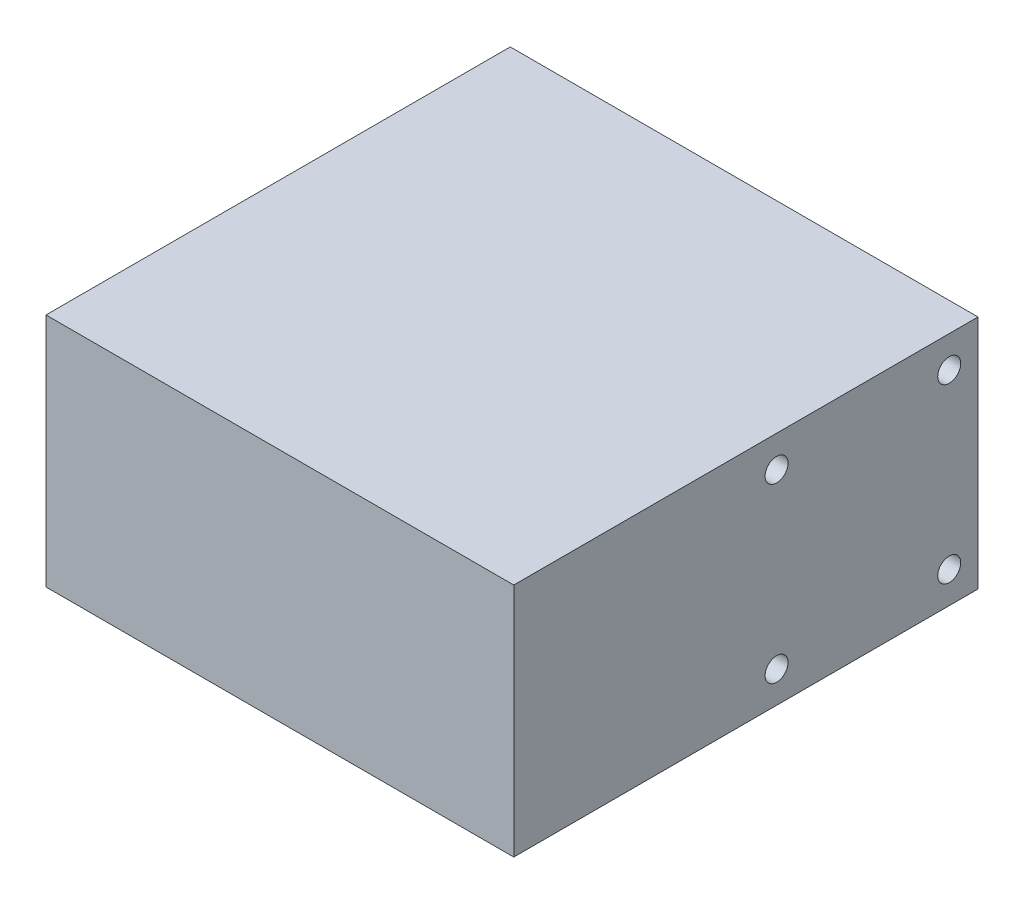
SolidWorks part; units mm, degrees
ref_plane "Front Plane" through (0, 0, 0) normal (0, 0, 1) x (1, 0, 0)
ref_plane "Top Plane" through (0, 0, 0) normal (0, 1, 0) x (1, 0, 0)
ref_plane "Right Plane" through (0, 0, 0) normal (1, 0, 0) x (0, 0, -1)
sketch "Sketch1" plane through (0, 0, 0) normal (0, 1, 0) x (1, 0, 0)
  line L1 (0, 0) -> (40.64, 0)
  line L2 (0, 0) -> (0, 40.3352)
  line L3 (0, 40.3352) -> (40.64, 40.3352)
  line L4 (40.64, 0) -> (40.64, 40.3352)
  dimension "D1" = 40.3352
  dimension "D2" = 40.64
extrude "Boss-Extrude1" add sketch "Sketch1" along normal blind 20.4724
sketch "Sketch3" plane through (0, 0, 0) normal (-1, 0, 0) x (0, 0, 1)
  line L0 (-40.3352, 20.4724) -> (0, 20.4724) construction
  line L2 (0, 20.4724) -> (0, 0) construction
  circle A0 centre (-10.541, 10.2362) radius 2.921
  circle A1 centre (-10.541, 10.2362) radius 0.6985
  dimension "D1" = 5.842
  dimension "D2" = 10.2362
  dimension "D4" = 1.397
  dimension "D3" = 10.541
extrude "Boss-Extrude2" add sketch "Sketch3" along normal blind 5.08
sketch "Sketch4" plane through (0, 0, 0) normal (-1, 0, 0) x (0, 0, 1)
  line L0 (-40.3352, 20.4724) -> (-40.3352, 0) construction
  line L4 (0, 0) -> (-40.3352, 0) construction
  circle A0 centre (-37.8352, 17.736) radius 1
  circle A1 centre (-37.8352, 2.736) radius 1
  circle A2 centre (-22.8352, 17.736) radius 1
  circle A3 centre (-22.8352, 2.736) radius 1
  dimension "D1" = 2
  dimension "D2" = 2
  dimension "D3" = 2.5
  dimension "D4" = 15
  dimension "D5" = 15
  dimension "D6" = 2.5
  dimension "D7" = 15
  dimension "D8" = 15
  dimension "D9" = 2
  dimension "D10" = 2
  dimension "D11" = 0
  dimension "D12" = 2.736
extrude "Cut-Extrude1" cut sketch "Sketch4" against normal through all
